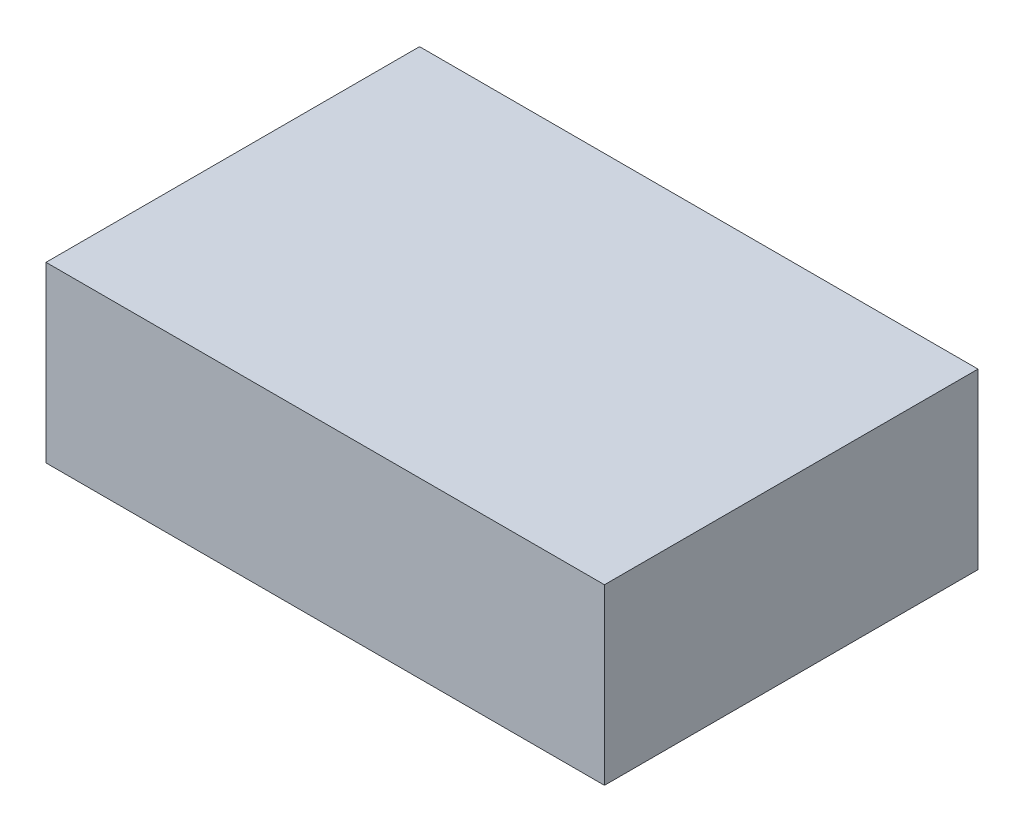
SolidWorks part; units mm, degrees
ref_plane "Front Plane" through (0, 0, 0) normal (0, 0, 1) x (1, 0, 0)
ref_plane "Top Plane" through (0, 0, 0) normal (0, 1, 0) x (1, 0, 0)
ref_plane "Right Plane" through (0, 0, 0) normal (1, 0, 0) x (0, 0, -1)
sketch "Sketch1" plane through (0, 0, 0) normal (0, 1, 0) x (1, 0, 0)
  line L1 (-45, 30.1) -> (45, 30.1)
  line L2 (-45, 30.1) -> (-45, -30.1)
  line L3 (-45, -30.1) -> (45, -30.1)
  line L4 (45, 30.1) -> (45, -30.1)
  line L5 (-45, 30.1) -> (45, -30.1) construction
  line L6 (-45, -30.1) -> (45, 30.1) construction
  point P0 (0, 0)
  dimension "D1" = 90
  dimension "D2" = 60.2
  dimension "D3" = 108.2776
extrude "Boss-Extrude1" add sketch "Sketch1" along normal blind 28
